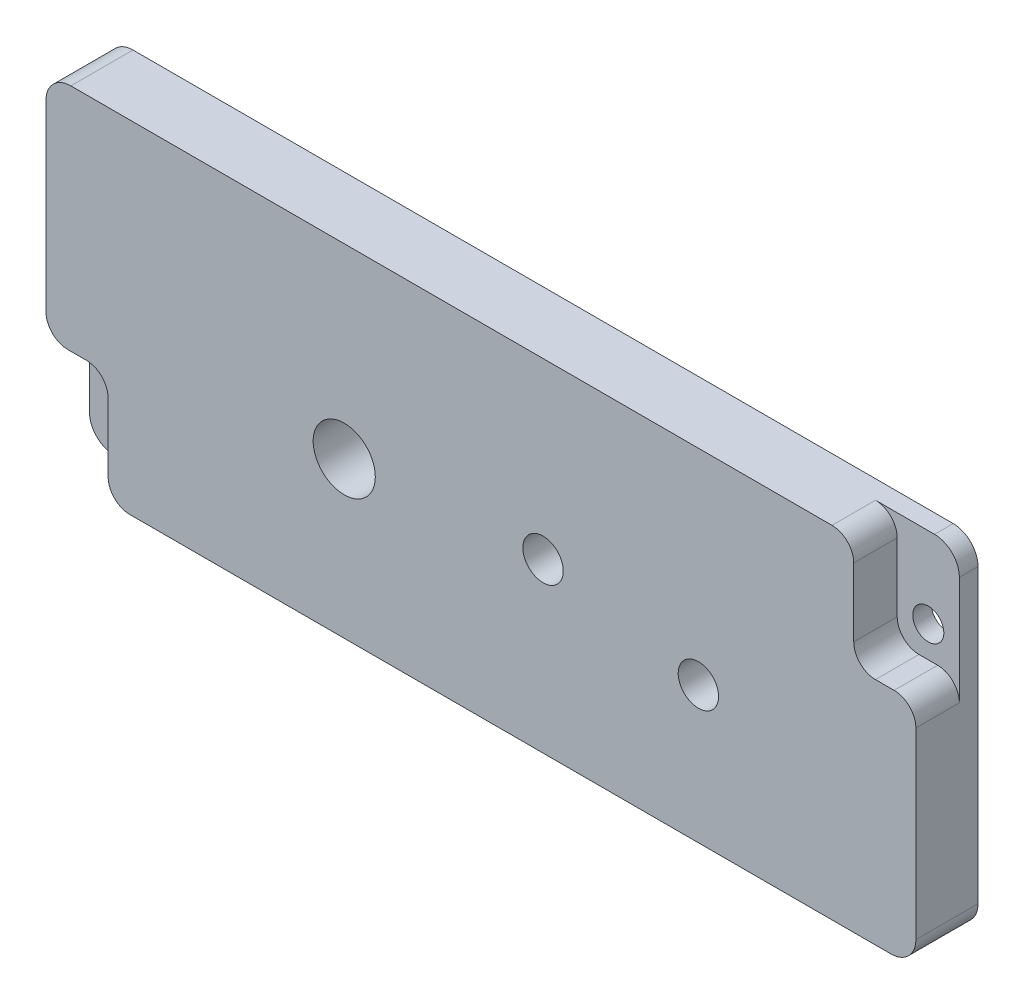
SolidWorks part; units mm, degrees
ref_plane "Front Plane" through (0, 0, 0) normal (0, 0, 1) x (1, 0, 0)
ref_plane "Top Plane" through (0, 0, 0) normal (0, 1, 0) x (1, 0, 0)
ref_plane "Right Plane" through (0, 0, 0) normal (1, 0, 0) x (0, 0, -1)
sketch "Sketch1" plane through (0, 0, 0) normal (0, 0, 1) x (1, 0, 0)
  line L1 (-73.7476, 33.9217) -> (58.2524, 33.9217)
  line L2 (-77.7476, 29.9217) -> (-77.7476, -17.0783)
  line L3 (-73.7476, -21.0783) -> (58.2524, -21.0783)
  line L4 (62.2524, 29.9217) -> (62.2524, -17.0783)
  arc A0 (58.2524, 33.9217) -> (62.2524, 29.9217) centre (58.2524, 29.9217) cw
  arc A1 (62.2524, -17.0783) -> (58.2524, -21.0783) centre (58.2524, -17.0783) cw
  arc A2 (-73.7476, -21.0783) -> (-77.7476, -17.0783) centre (-73.7476, -17.0783) cw
  arc A3 (-77.7476, 29.9217) -> (-73.7476, 33.9217) centre (-73.7476, 29.9217) cw
  circle A4 centre (-29.7476, 3.9217) radius 5
  circle A5 centre (2.2524, 5.9217) radius 3.25
  circle A6 centre (27.2524, 0.9217) radius 3.25
  point P6 (62.2524, 33.9217)
  point P11 (-77.7476, -21.0783)
  point P14 (-77.7476, 33.9217)
  dimension "D3" = 4
  dimension "D6" = 10
  dimension "D9" = 80
  dimension "D7" = 6.5
  dimension "D12" = 6.5
  dimension "D1" = 140
  dimension "D2" = 55
  dimension "D4" = 48
  dimension "D5" = 30
  dimension "D8" = 28
  dimension "D10" = 105
  dimension "D11" = 33
extrude "Boss-Extrude1" add sketch "Sketch1" along normal blind 10
sketch "Sketch2" plane through (0, 0, 10) normal (0, 0, 1) x (1, 0, 0)
  line L0 (-77.7476, 29.9217) -> (-77.7476, -17.0783) construction
  line L5 (58.2524, 33.9217) -> (-73.7476, 33.9217) construction
  line L6 (-73.7476, -21.0783) -> (58.2524, -21.0783) construction
  line L7 (-77.7476, -3.0783) -> (-71.2476, -3.0783)
  line L8 (-77.7476, -3.0783) -> (-77.7476, -21.0783)
  line L9 (-77.7476, -21.0783) -> (-67.7476, -21.0783)
  line L10 (-67.7476, -6.5783) -> (-67.7476, -21.0783)
  line L11 (62.2524, -17.0783) -> (62.2524, 29.9217) construction
  line L17 (62.2524, 15.9217) -> (55.7524, 15.9217)
  line L18 (62.2524, 15.9217) -> (62.2524, 33.9217)
  line L19 (62.2524, 33.9217) -> (52.2524, 33.9217)
  line L20 (52.2524, 19.4217) -> (52.2524, 33.9217)
  arc A0 (-71.2476, -3.0783) -> (-67.7476, -6.5783) centre (-71.2476, -6.5783) cw
  arc A2 (55.7524, 15.9217) -> (52.2524, 19.4217) centre (55.7524, 19.4217) cw
  point P26 (-67.7476, -3.0783)
  point P29 (52.4234, -11.0783)
  point P32 (52.2524, 15.9217)
  point P35 (-67.7476, 23.9217)
  dimension "D9" = 3.5
  dimension "D3" = 18
  dimension "D4" = 10
  dimension "D7" = 10
  dimension "D8" = 18
extrude "Cut-Extrude1" cut sketch "Sketch2" against normal blind 7
sketch "Sketch3" plane through (0, 0, 3) normal (0, 0, 1) x (1, 0, 0)
  line L0 (-71.2476, -3.0783) -> (-77.7476, -3.0783) construction
  line L1 (-67.7476, -21.0783) -> (-67.7476, -6.5783) construction
  line L2 (52.2524, 33.9217) -> (52.2524, 19.4217) construction
  line L3 (55.7524, 15.9217) -> (62.2524, 15.9217) construction
  circle A0 centre (-72.7476, -8.0783) radius 2.5
  circle A1 centre (57.2524, 20.9217) radius 2.5
  dimension "D3" = 5
  dimension "D6" = 5
  dimension "D1" = 5
  dimension "D2" = 5
  dimension "D4" = 5
  dimension "D5" = 5
extrude "Cut-Extrude2" cut sketch "Sketch3" against normal blind 10
fillet "Fillet1" radius 3.5 4 edges at (62.2524, 15.9217, 6.5) (52.2524, 33.9217, 6.5) (-67.7476, -21.0783, 6.5) (-77.7476, -3.0783, 6.5)
